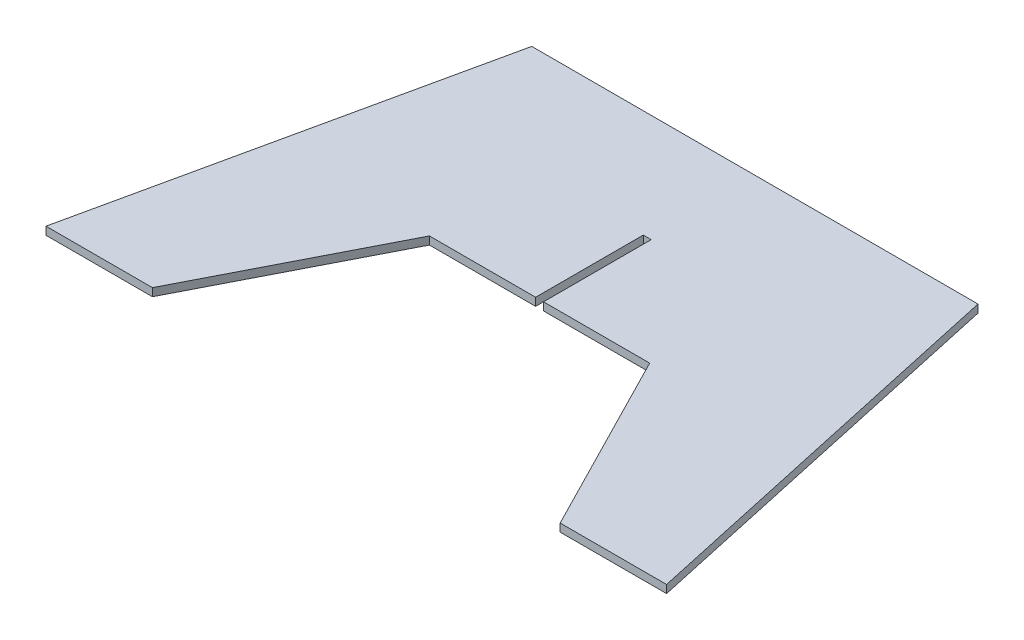
SolidWorks part; units mm, degrees
material "201 Annealed Stainless Steel (SS)"
ref_plane "Front Plane" through (0, 0, 0) normal (0, 0, 1) x (1, 0, 0)
ref_plane "Top Plane" through (0, 0, 0) normal (0, 1, 0) x (1, 0, 0)
ref_plane "Right Plane" through (0, 0, 0) normal (1, 0, 0) x (0, 0, -1)
sketch "Sketch1" plane through (0, 0, 0) normal (0, 1, 0) x (1, 0, 0)
  line L0 (-22.25, 0) -> (-33.8636, 0)
  line L1 (-33.8636, 0) -> (-24.35, 43.5)
  line L2 (-24.35, 43.5) -> (24.35, 43.5)
  line L3 (24.35, 43.5) -> (33.8636, 0)
  line L4 (33.8636, 0) -> (22.25, 0)
  line L5 (22.25, 0) -> (12.0201, 20)
  line L6 (12.0201, 20) -> (-12.0201, 20)
  line L7 (-12.0201, 20) -> (-22.25, 0)
  line L8 (0, 43.5) -> (0, 20) construction
  line L9 (0, 20) -> (0, 0) construction
  line L10 (0, 43.5) -> (-22.25, 0) construction
  line L11 (0.4318, 31.75) -> (0.4318, 43.5) construction
  line L12 (0.4318, 20) -> (-0.4318, 20)
  line L13 (0.4318, 20) -> (0.4318, 31.75)
  line L14 (0.4318, 31.75) -> (-0.4318, 31.75)
  line L15 (-0.4318, 20) -> (-0.4318, 31.75)
  point P10 (0, 31.75)
  dimension "D1" = 67.7272
  dimension "D2" = 48.7
  dimension "D3" = 43.5
  dimension "D4" = 44.5
  dimension "D5" = 20
  dimension "D6" = 0.8636
extrude "Boss-Extrude1" add sketch "Sketch1" along normal blind 0.8636 contours L6 L15 L14 L13 L5 L4 L3 L2 L1 L0 L7
